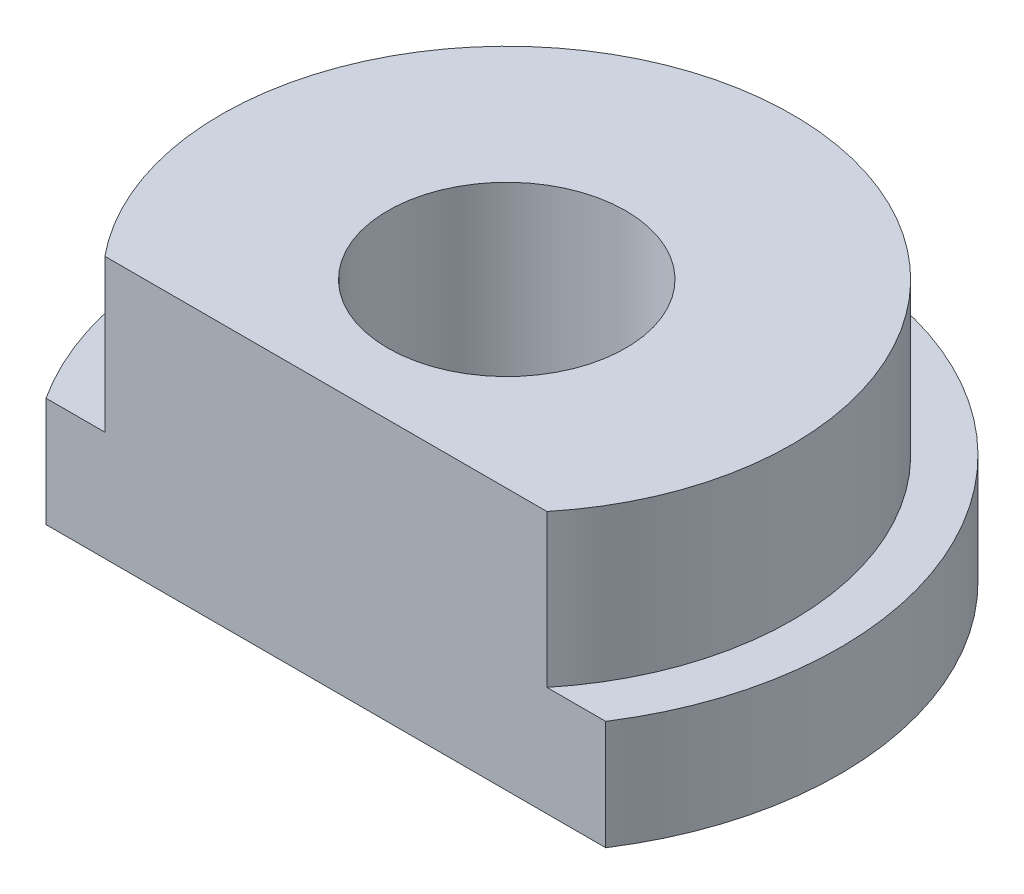
SolidWorks part; units mm, degrees
material "ﾏﾝｶﾞﾝ青銅"
ref_plane "正面" through (0, 0, 0) normal (0, 0, 1) x (1, 0, 0)
ref_plane "平面" through (0, 0, 0) normal (0, 1, 0) x (1, 0, 0)
ref_plane "右側面" through (0, 0, 0) normal (1, 0, 0) x (0, 0, -1)
sketch "ｽｹｯﾁ1" plane through (0, 0, 0) normal (0, 0, 1) x (1, 0, 0)
  line L0 (1.25, 0) -> (1.25, 2.75)
  line L1 (1.25, 2.75) -> (3, 2.75)
  line L2 (3, 2.75) -> (3, 1.15)
  line L3 (3, 1.15) -> (3.5, 1.15)
  line L4 (3.5, 1.15) -> (3.5, 0)
  line L5 (3.5, 0) -> (1.25, 0)
  line L6 (0, 0) -> (0, 2.75) construction
  dimension "D1" = 2.75
  dimension "D2" = 1.15
  dimension "D3" = 3.5
  dimension "D4" = 3
  dimension "D5" = 1.25
revolve "回転1" add sketch "ｽｹｯﾁ1" angle 360 about L6
sketch "ｽｹｯﾁ2" plane through (0, 2.75, 0) normal (0, 1, 0) x (1, 0, 0)
  line L0 (-2.9394, -1.9) -> (2.9394, -1.9)
  circle A0 centre (0, 0) radius 3.5 construction
  arc A1 (-2.9394, -1.9) -> (2.9394, -1.9) centre (0, 0) ccw
  dimension "D1" = 1.9
extrude "ｶｯﾄ - 押し出し1" cut sketch "ｽｹｯﾁ2" against normal through all
